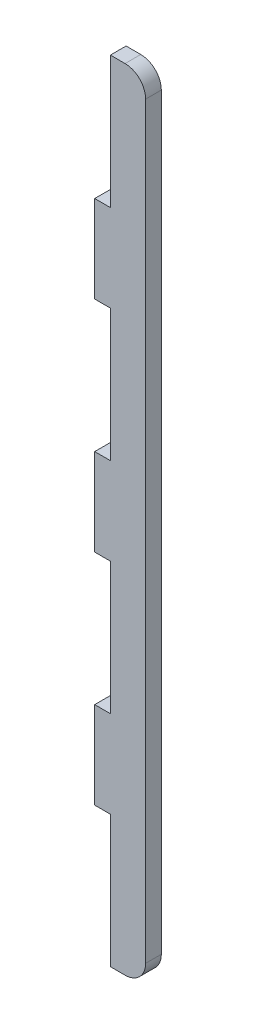
SolidWorks part; units mm, degrees
ref_plane "Front Plane" through (0, 0, 0) normal (0, 0, 1) x (1, 0, 0)
ref_plane "Top Plane" through (0, 0, 0) normal (0, 1, 0) x (1, 0, 0)
ref_plane "Right Plane" through (0, 0, 0) normal (1, 0, 0) x (0, 0, -1)
sketch "Model" plane through (0, 0, 0) normal (0, 0, 1) x (1, 0, 0)
  line L4 (10.35, 269) -> (5.35, 269)
  line L5 (17.35, 7) -> (17.35, 262)
  line L6 (5.35, 0) -> (10.35, 0)
  line L7 (5.35, 45) -> (5.35, 0)
  line L8 (0, 45) -> (5.35, 45)
  line L9 (0, 74.6667) -> (0, 45)
  line L10 (5.35, 74.6667) -> (0, 74.6667)
  line L11 (5.35, 119.6667) -> (5.35, 74.6667)
  line L12 (0, 119.6667) -> (5.35, 119.6667)
  line L13 (0, 149.3333) -> (0, 119.6667)
  line L14 (5.35, 149.3333) -> (0, 149.3333)
  line L15 (5.35, 194.3333) -> (5.35, 149.3333)
  line L16 (0, 194.3333) -> (5.35, 194.3333)
  line L17 (0, 224) -> (0, 194.3333)
  line L18 (5.35, 224) -> (0, 224)
  line L19 (5.35, 269) -> (5.35, 224)
  arc A0 (10.35, 0) -> (17.35, 7) centre (10.35, 7) ccw
  arc A1 (17.35, 262) -> (10.35, 269) centre (10.35, 262) ccw
extrude "Boss-Extrude1" add sketch "Model" along normal blind 5.35
